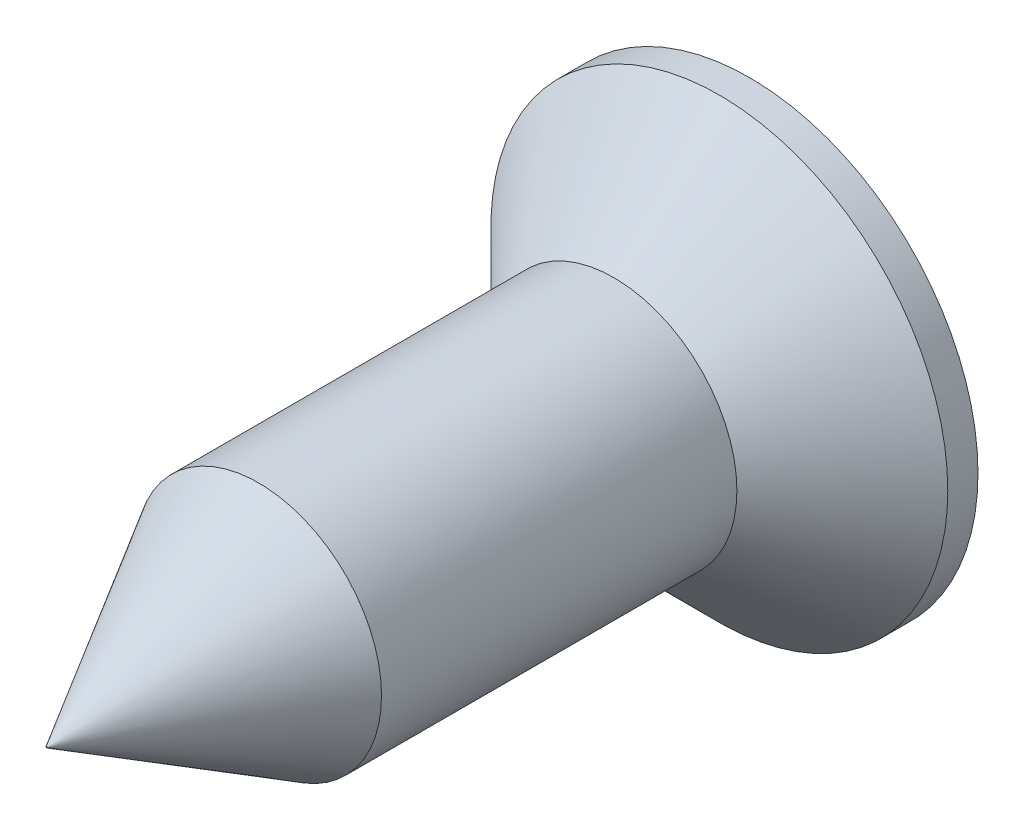
SolidWorks part; units mm, degrees
ref_plane "Front" through (0, 0, 0) normal (0, 0, 1) x (1, 0, 0)
ref_plane "Top" through (0, 0, 0) normal (0, 1, 0) x (1, 0, 0)
ref_plane "Right" through (0, 0, 0) normal (1, 0, 0) x (0, 0, -1)
sketch "Sketch1" plane through (0, 0, 0) normal (0, 1, 0) x (1, 0, 0)
  line L0 (0, 0) -> (0, -10)
  line L1 (0.01, -10) -> (1.75, -6.9862)
  line L2 (1.75, -6.9862) -> (1.75, -1.93)
  line L3 (1.75, -1.93) -> (3.25, -0.43)
  line L4 (3.25, 0) -> (0, 0)
  line L5 (0, 0) -> (0, 3.3237) construction
  line L6 (0, -10) -> (0.01, -10)
  line L7 (3.25, 0) -> (3.25, -0.43)
  dimension "D1" = 30
  dimension "D3" = 45
  dimension "D" = 3.5
  dimension "L" = 10
  dimension "D7" = 0.01
  dimension "DG" = 6.5
  dimension "HG" = 1.93
revolve "Revolve1" add sketch "Sketch1" angle 360 about L5
sketch "Sketch2" plane through (0, 0, 0) normal (0, 0, -1) x (-1, 0, 0)
  line L0 (-0.35, 0.5833) -> (-0.35, 0.8459)
  line L1 (-0.35, 0.8459) -> (0.35, 0.8459)
  line L2 (0.35, 0.8459) -> (0.35, 0.5833)
  line L3 (0.5833, 0.35) -> (0.8459, 0.35)
  line L4 (0.8459, 0.35) -> (0.8459, -0.35)
  line L5 (0.8459, -0.35) -> (0.5833, -0.35)
  line L6 (0.35, -0.5833) -> (0.35, -0.8459)
  line L7 (0.35, -0.8459) -> (-0.35, -0.8459)
  line L8 (-0.35, -0.8459) -> (-0.35, -0.5833)
  line L9 (-0.5833, -0.35) -> (-0.8459, -0.35)
  line L10 (-0.8459, -0.35) -> (-0.8459, 0.35)
  line L11 (-0.8459, 0.35) -> (-0.5833, 0.35)
  arc A0 (0.5833, 0.35) -> (0.35, 0.5833) centre (0.5833, 0.5833) cw
  arc A1 (0.35, -0.5833) -> (0.5833, -0.35) centre (0.5833, -0.5833) cw
  arc A2 (-0.5833, -0.35) -> (-0.35, -0.5833) centre (-0.5833, -0.5833) cw
  arc A3 (-0.35, 0.5833) -> (-0.5833, 0.35) centre (-0.5833, 0.5833) cw
  circle A4 centre (0, 0) radius 0.5916 construction
  circle A5 centre (0, 0) radius 3.25 construction
  dimension "D1" = 0.2333
  dimension "D2" = 0.7
  dimension "D3" = 0.2626
extrude "Cut-Extrude1" cut sketch "Sketch2" against normal blind 1.737
draft "Draft1" type of draft neutral plane draft angle 45 faces to draft 4 face at (0, -0.8459, 0.8685) face at (-0.8459, 0, 0.8685) face at (0.8459, 0, 0.8685) face at (0, 0.8459, 0.8685) neutral plane through (-0.5833, 0.5833, 1.737) neutral plane normal (0, 0, -1) parameters "D1"=45
sketch "Sketch3" plane through (0, 0, 0) normal (0, 0, 1) x (1, 0, 0)
  line L0 (0, 0) -> (0, 8.8707) construction
  line L1 (-2.649, -1.8829) -> (1.8829, 2.649)
  line L2 (-1.8829, -2.649) -> (2.649, 1.8829)
  arc A1 (2.649, 1.8829) -> (1.8829, 2.649) centre (0, 0) ccw
  arc A2 (-2.649, -1.8829) -> (-1.8829, -2.649) centre (0, 0) ccw
  circle A3 centre (0, 0) radius 3.25 construction
  dimension "D1" = 45
  dimension "D2" = 1.0833
extrude "Cut-Extrude2" [suppressed] cut sketch "Sketch3" along normal blind 1.544
equation "\"D2@Sketch2\" = \"D@Sketch1\"/5"
equation "\"D3@Sketch2\" = \"D@Sketch1\"/13.33"
equation "\"D1@Sketch2\" = \"D@Sketch1\"/15"
equation "\"D1@Cut-Extrude1\" = \"HG@Sketch1\"*0.9"
equation "\"D2@Sketch3\" = \"DG@Sketch1\"/6"
equation "\"D1@Cut-Extrude2\"=\"HG@Sketch1\"*0.8"
